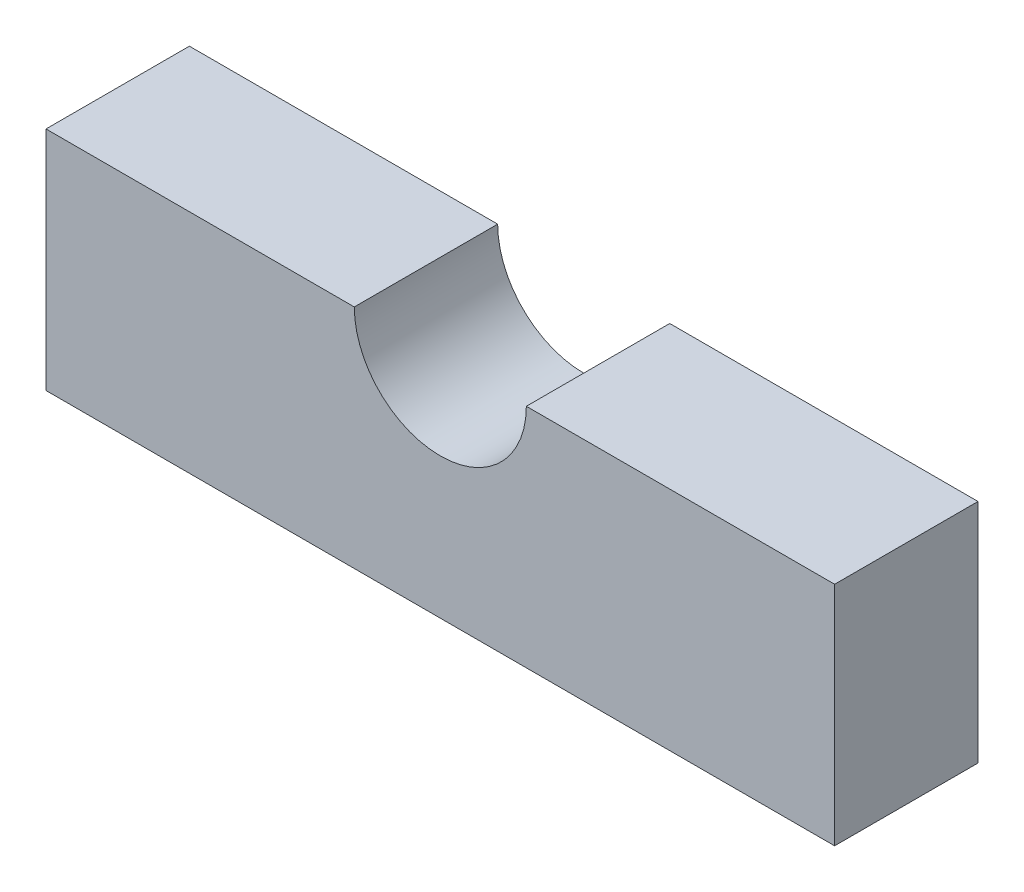
SolidWorks part; units mm, degrees
ref_plane "Front" through (0, 0, 0) normal (0, 0, 1) x (1, 0, 0)
ref_plane "Top" through (0, 0, 0) normal (0, 1, 0) x (1, 0, 0)
ref_plane "Right" through (0, 0, 0) normal (1, 0, 0) x (0, 0, -1)
sketch "Sketch1" plane through (0, 0, 0) normal (0, 1, 0) x (1, 0, 0)
  line L1 (34.925, -6.35) -> (-34.925, -6.35)
  line L2 (34.925, -6.35) -> (34.925, 6.35)
  line L3 (34.925, 6.35) -> (-34.925, 6.35)
  line L4 (-34.925, -6.35) -> (-34.925, 6.35)
  line L5 (34.925, -6.35) -> (-34.925, 6.35) construction
  line L6 (34.925, 6.35) -> (-34.925, -6.35) construction
  point P0 (0, 0)
  dimension "D1" = 12.7
  dimension "D2" = 69.85
extrude "Boss-Extrude1" add sketch "Sketch1" along normal blind 20.066
sketch "Sketch3" plane through (0, 0, -6.35) normal (0, 0, -1) x (-1, 0, 0)
  line L0 (-34.925, 20.066) -> (34.925, 20.066) construction
  circle A0 centre (0, 20.066) radius 7.62
  dimension "D1" = 15.24
extrude "Cut-Extrude3" cut sketch "Sketch3" against normal blind 25.4
sketch "Sketch4" plane through (0, 0, 0) normal (0, -1, 0) x (-1, 0, 0)
  line L0 (-11.0363, 0) -> (11.0363, 0) construction
  line L1 (0, 6.985) -> (0, -6.985) construction
  circle A0 centre (25.4, 0) radius 1.27
  circle A1 centre (-25.4, 0) radius 1.27
  dimension "D3" = 2.54
  dimension "D4" = 2.54
  dimension "D1" = 25.4
  dimension "D2" = 25.4
extrude "Cut-Extrude4" cut sketch "Sketch4" against normal blind 5.08
